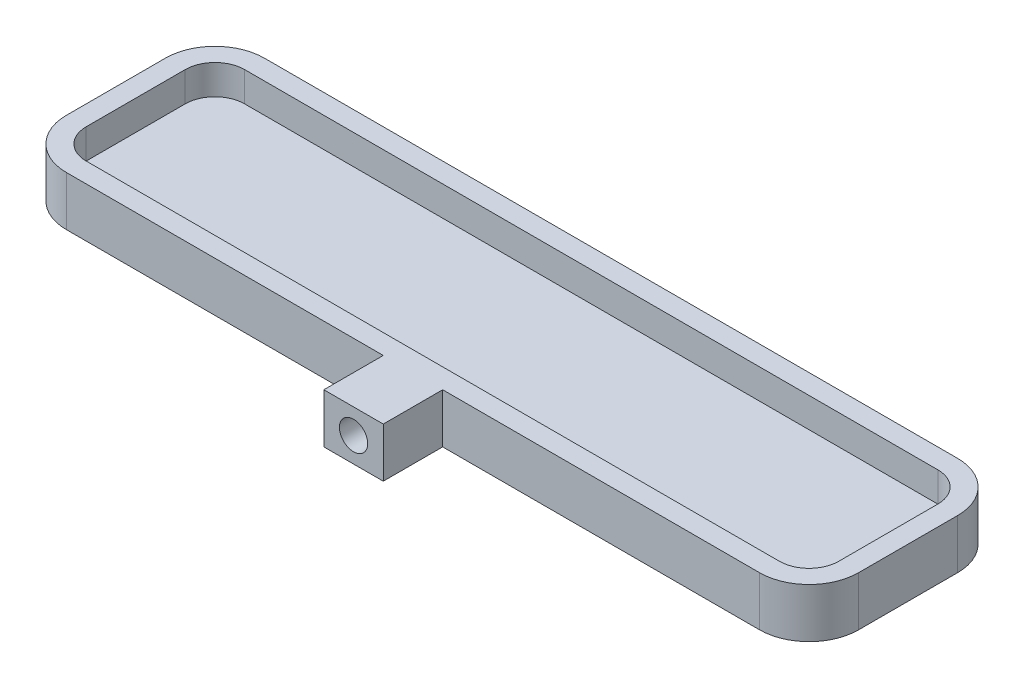
SolidWorks part; units mm, degrees
ref_plane "Front Plane" through (0, 0, 0) normal (0, 0, 1) x (1, 0, 0)
ref_plane "Top Plane" through (0, 0, 0) normal (0, 1, 0) x (1, 0, 0)
ref_plane "Right Plane" through (0, 0, 0) normal (1, 0, 0) x (0, 0, -1)
sketch "Sketch1" plane through (0, 0, 0) normal (0, 1, 0) x (1, 0, 0)
  line L1 (-40, -10) -> (40, -10)
  line L2 (-40, -10) -> (-40, 10)
  line L3 (-40, 10) -> (40, 10)
  line L4 (40, -10) -> (40, 10)
  line L5 (-40, -10) -> (40, 10) construction
  line L6 (-40, 10) -> (40, -10) construction
  point P0 (0, 0)
  dimension "D1" = 80
  dimension "D2" = 20
extrude "Boss-Extrude1" add sketch "Sketch1" along normal blind 5
fillet "Fillet1" radius 5 4 edges at (40, 2.5, -10) (40, 2.5, 10) (-40, 2.5, 10) (-40, 2.5, -10)
shell "Shell1" thickness 2
sketch "Sketch2" plane through (0, 0, 10) normal (0, 0, 1) x (1, 0, 0)
  line L0 (0, 0) -> (0, 5) construction
  line L1 (-35, 5) -> (35, 5) construction
  line L3 (-3, 0) -> (3, 0)
  line L4 (-3, 0) -> (-3, 5)
  line L5 (-3, 5) -> (3, 5)
  line L6 (3, 0) -> (3, 5)
  line L7 (-3, 0) -> (3, 5) construction
  line L8 (-3, 5) -> (3, 0) construction
  point P5 (0, 2.5)
  dimension "D1" = 6
extrude "Boss-Extrude2" add sketch "Sketch2" along normal blind 6
sketch "Sketch3" plane through (0, 0, 16) normal (0, 0, 1) x (1, 0, 0)
  line L0 (0, 0) -> (0, 5) construction
  line L1 (3, 5) -> (-3, 5) construction
  circle A0 centre (0, 2.5) radius 1.425
  dimension "D1" = 2.85
extrude "Cut-Extrude1" cut sketch "Sketch3" against normal blind 4
